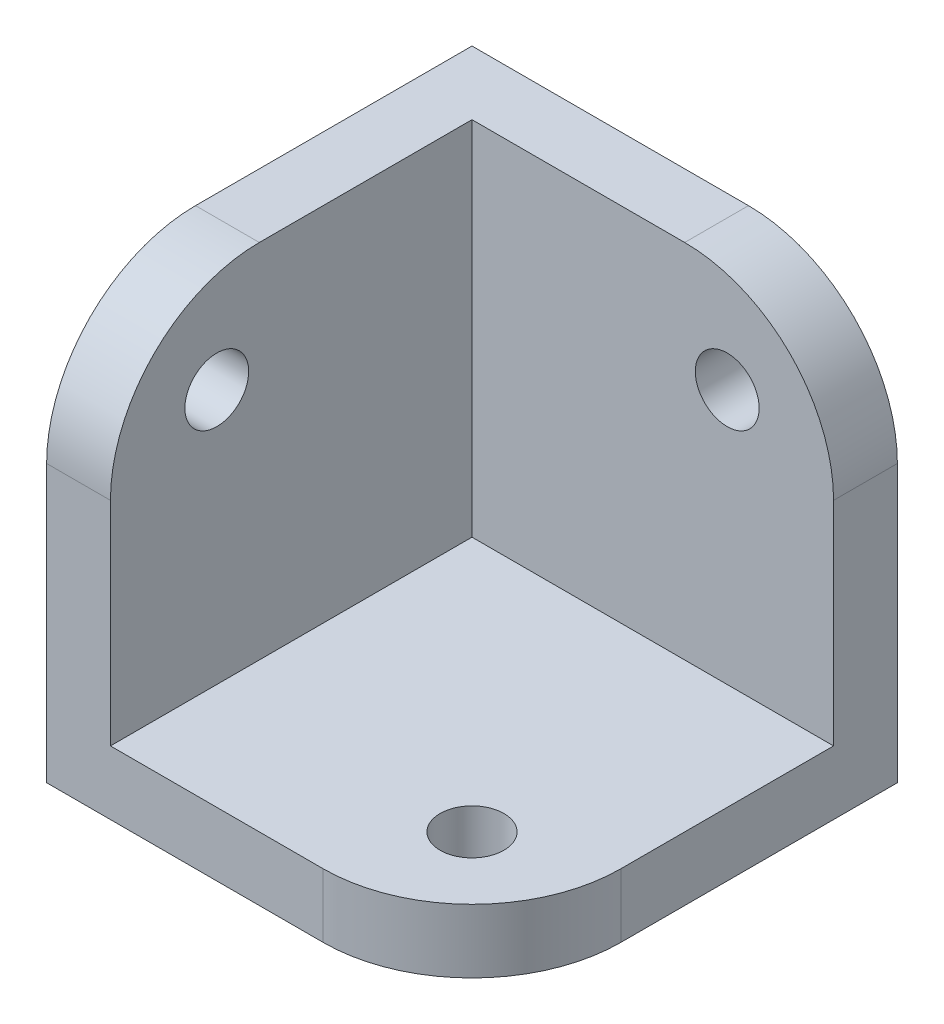
SolidWorks part; units mm, degrees
ref_plane "Front Plane" through (0, 0, 0) normal (0, 0, 1) x (1, 0, 0)
ref_plane "Top Plane" through (0, 0, 0) normal (0, 1, 0) x (1, 0, 0)
ref_plane "Right Plane" through (0, 0, 0) normal (1, 0, 0) x (0, 0, -1)
sketch "Sketch1" plane through (0, 0, 0) normal (0, 0, 1) x (1, 0, 0)
  line L0 (0, 0) -> (20, 0)
  line L1 (20, 0) -> (20, 20)
  line L2 (20, 20) -> (0, 20)
  line L3 (0, 20) -> (0, 0)
extrude "Boss-Extrude1" add sketch "Sketch1" along normal blind 3
sketch "Sketch2" plane through (0, 0, 3) normal (0, 0, 1) x (1, 0, 0)
  line L0 (0, 20) -> (3, 20)
  line L1 (20, 20) -> (0, 20) construction
  line L2 (3, 20) -> (3, 3)
  line L3 (3, 3) -> (20, 3)
  line L4 (20, 3) -> (20, 0)
  line L5 (20, 0) -> (0, 0)
  line L6 (0, 0) -> (0, 20)
extrude "Boss-Extrude2" add sketch "Sketch2" along normal blind 17
sketch "Sketch3" plane through (0, 0, 0) normal (-1, 0, 0) x (0, 0, 1)
  circle A0 centre (15, 15) radius 1.5
extrude "Cut-Extrude1" cut sketch "Sketch3" against normal blind 17
sketch "Sketch4" plane through (0, 0, 0) normal (0, 0, -1) x (-1, 0, 0)
  circle A0 centre (-15, 15) radius 1.5
extrude "Cut-Extrude2" cut sketch "Sketch4" against normal blind 17
sketch "Sketch5" plane through (0, 0, 0) normal (0, -1, 0) x (-1, 0, 0)
  circle A0 centre (-15, -15) radius 1.5
extrude "Cut-Extrude3" cut sketch "Sketch5" against normal blind 17
fillet "Fillet1" radius 7 3 edges at (20, 1.5, 20) (1.5, 20, 20) (20, 20, 1.5)
